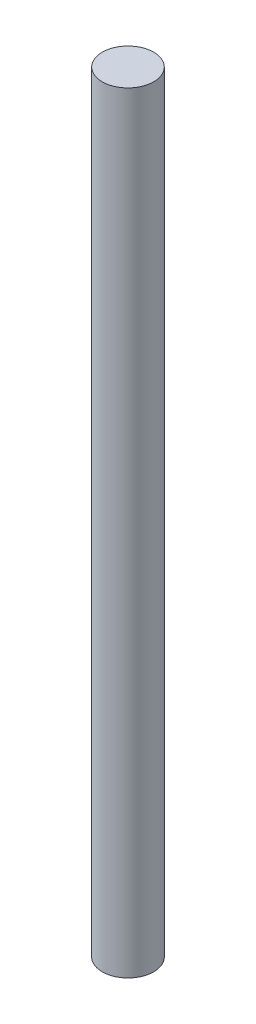
SolidWorks part; units mm, degrees
ref_plane "Front Plane" through (0, 0, 0) normal (0, 0, 1) x (1, 0, 0)
ref_plane "Top Plane" through (0, 0, 0) normal (0, 1, 0) x (1, 0, 0)
ref_plane "Right Plane" through (0, 0, 0) normal (1, 0, 0) x (0, 0, -1)
sketch "Sketch2" plane through (0, 0, 0) normal (0, 1, 0) x (1, 0, 0)
  circle A0 centre (0, 0) radius 5
  dimension "D1" = 10
extrude "Boss-Extrude1" add sketch "Sketch2" along normal blind 150
